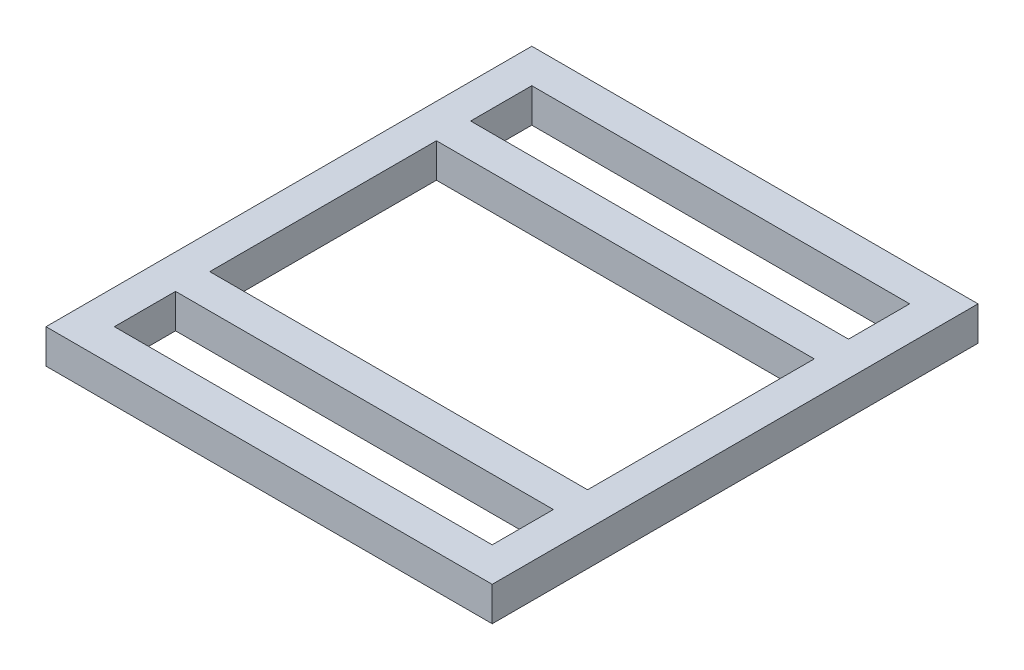
SolidWorks part; units mm, degrees
ref_plane "Front Plane" through (0, 0, 0) normal (0, 0, 1) x (1, 0, 0)
ref_plane "Top Plane" through (0, 0, 0) normal (0, 1, 0) x (1, 0, 0)
ref_plane "Right Plane" through (0, 0, 0) normal (1, 0, 0) x (0, 0, -1)
sketch "Sketch1" plane through (0, 0, 0) normal (0, 1, 0) x (1, 0, 0)
  line L0 (-44.335, 191.7647) -> (-44.335, -78.2353)
  line L1 (-44.335, -78.2353) -> (-25.335, -78.2353)
  line L2 (-25.335, -59.2353) -> (-25.335, -25.2353)
  line L3 (-25.335, -25.2353) -> (184.665, -25.2353)
  line L4 (184.665, -25.2353) -> (184.665, -59.2353)
  line L5 (184.665, -78.2353) -> (203.665, -78.2353)
  line L6 (203.665, -78.2353) -> (203.665, 191.7647)
  line L7 (203.665, 191.7647) -> (184.665, 191.7647)
  line L8 (184.665, 172.7647) -> (184.665, 138.7647)
  line L9 (184.665, 138.7647) -> (-25.335, 138.7647)
  line L10 (-25.335, 138.7647) -> (-25.335, 172.7647)
  line L11 (-25.335, 191.7647) -> (-44.335, 191.7647)
  line L12 (-25.335, 119.7647) -> (184.665, 119.7647)
  line L13 (184.665, 119.7647) -> (184.665, -6.2353)
  line L14 (184.665, -6.2353) -> (-25.335, -6.2353)
  line L15 (-25.335, -6.2353) -> (-25.335, 119.7647)
  line L16 (-25.335, -78.2353) -> (184.665, -78.2353)
  line L17 (184.665, -59.2353) -> (-25.335, -59.2353)
  line L18 (-25.335, 191.7647) -> (184.665, 191.7647)
  line L19 (-25.335, 172.7647) -> (184.665, 172.7647)
  dimension "D1" = 19
  dimension "D2" = 19
  dimension "D3" = 19
  dimension "D4" = 19
  dimension "D5" = 270
  dimension "D6" = 34
  dimension "D7" = 19
  dimension "D8" = 19
  dimension "D9" = 34
  dimension "D10" = 248
  dimension "D11" = 19
  dimension "D12" = 19
  dimension "D13" = 19
extrude "Boss-Extrude1" add sketch "Sketch1" along normal blind 19
